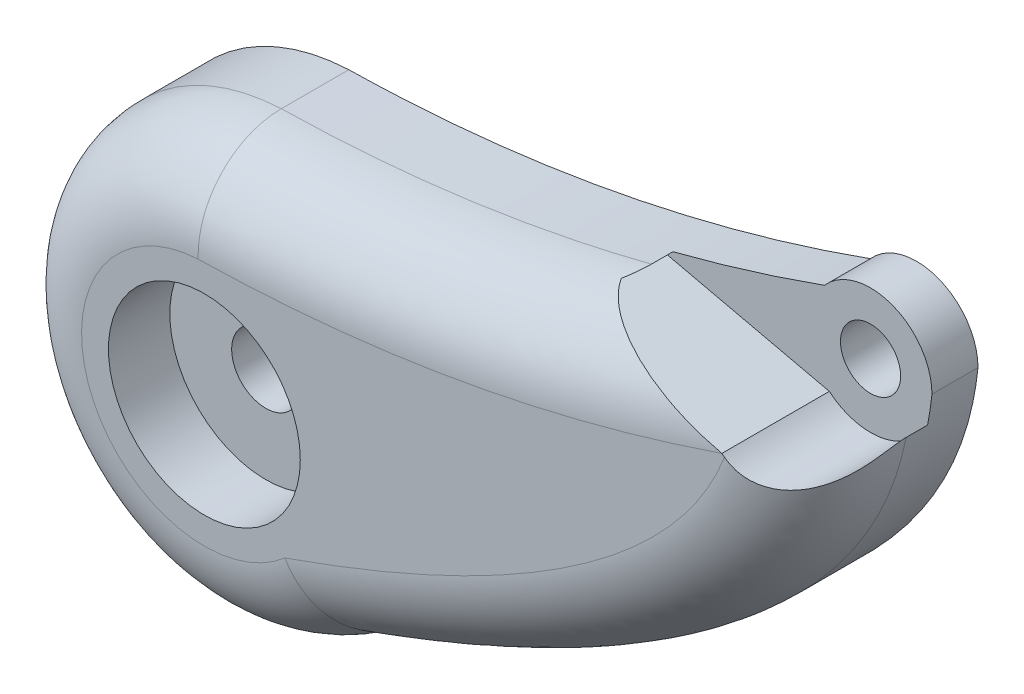
SolidWorks part; units mm, degrees
ref_plane "Front Plane" through (0, 0, 0) normal (0, 0, 1) x (1, 0, 0)
ref_plane "Top Plane" through (0, 0, 0) normal (0, 1, 0) x (1, 0, 0)
ref_plane "Right Plane" through (0, 0, 0) normal (1, 0, 0) x (0, 0, -1)
sketch "Sketch1" plane through (0, 0, 0) normal (0, 0, 1) x (1, 0, 0)
  arc A0 (0, 8.636) -> (5.0652, -6.9946) centre (0, 0) ccw
  arc A1 (25.572, 10.3301) -> (21.2053, 12.6462) centre (23.114, 10.9704) ccw
  circle A2 centre (23.114, 10.9704) radius 1.244
  circle A3 centre (0, 0) radius 1.4115
  spline S0 degree 3 poles (5.0652, -6.9946) (18.0309, -2.3804) (24.8939, 3.6079) (25.654, 10.9704) knots 0.062602 0.062602 0.062602 0.062602 0.571199 0.571199 0.571199 0.571199
  spline S1 degree 3 poles (21.2053, 12.6462) (14.2558, 10.1483) (7.0651, 8.7884) (-0.2488, 8.6303) (-0.3733, 8.6279) knots 0.085211 0.085211 0.085211 0.085211 0.879863 0.893616 0.893616 0.893616 0.893616
  dimension "D1" = 17.272
  dimension "D3" = 5.08
extrude "Boss-Extrude1" add sketch "Sketch1" along normal blind 8.89
sketch "Sketch2" plane through (0, 0, 8.89) normal (0, 0, 1) x (1, 0, 0)
  circle A0 centre (23.114, 10.9704) radius 2.6456
extrude "Cut-Extrude1" cut sketch "Sketch2" against normal blind 4.445
fillet "Fillet1" radius 3.556 3 edges at (-8.1559, -2.8392, 8.89)
sketch "Sketch3" plane through (0, 0, 0) normal (0, 0, -1) x (-1, 0, 0)
  line L1 (13.9717, -14.1873) -> (-30.7033, -14.1873)
  line L2 (13.9717, -14.1873) -> (13.9717, 17.4811)
  line L3 (13.9717, 17.4811) -> (-30.7033, 17.4811)
  line L4 (-30.7033, -14.1873) -> (-30.7033, 17.4811)
extrude "Cut-Extrude2" cut sketch "Sketch3" against normal blind 2.54
sketch "Sketch4" plane through (0, 0, 8.89) normal (0, 0, 1) x (1, 0, 0)
  circle A0 centre (0, 0) radius 3.9688
  dimension "D1" = 7.9375
extrude "Cut-Extrude3" cut sketch "Sketch4" against normal blind 2.54
sketch "Sketch9" plane through (0, 0, 8.89) normal (0, 0, 1) x (1, 0, 0)
  line L0 (21.4081, 8.9482) -> (14.6165, 10.5089)
  line L1 (14.6165, 10.5089) -> (20.7911, 14.493)
  line L2 (20.7911, 14.493) -> (23.3247, 10.8274)
  line L3 (23.3247, 10.8274) -> (21.4081, 8.9482)
  spline S0 degree 3 poles (21.4081, 8.9482) (17.9232, 7.7507) (14.3535, 6.8127) (7.1028, 5.5093) (3.4277, 5.1455) (-0.2567, 5.0735) knots 0 0 0 0 0.5 0.5 1 1 1 1 construction
extrude "Cut-Extrude7" cut sketch "Sketch9" against normal blind 4.445
